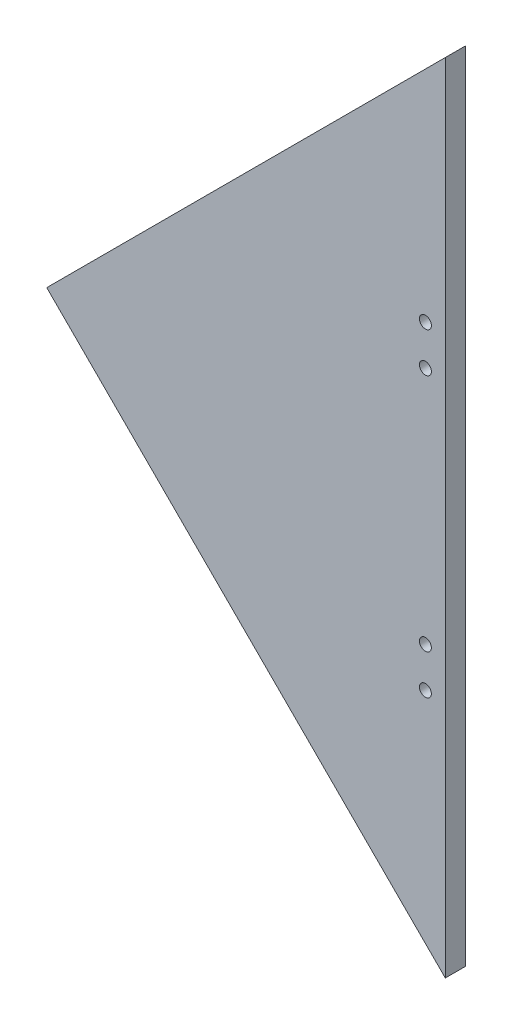
SolidWorks part; units mm, degrees
ref_plane "Front Plane" through (0, 0, 0) normal (0, 0, 1) x (1, 0, 0)
ref_plane "Top Plane" through (0, 0, 0) normal (0, 1, 0) x (1, 0, 0)
ref_plane "Right Plane" through (0, 0, 0) normal (1, 0, 0) x (0, 0, -1)
sketch "Sketch2" plane through (0, 0, 0) normal (0, 0, 1) x (1, 0, 0)
  line L0 (0, -100) -> (0, 100)
  line L1 (0, 100) -> (-100, 0)
  line L2 (-100, 0) -> (0, -100)
  line L3 (-5, 95) -> (-5, -95) construction
  line L4 (0, 0) -> (-100, 0) construction
  circle A0 centre (-5, 40) radius 1.5
  circle A1 centre (-5, 30) radius 1.5
  circle A2 centre (-5, -30) radius 1.5
  circle A3 centre (-5, -40) radius 1.5
  dimension "D3" = 3
  dimension "D1" = 200
  dimension "D2" = 100
  dimension "D4" = 30
  dimension "D5" = 10
  dimension "D6" = 5
extrude "Boss-Extrude1" add sketch "Sketch2" along normal blind 5
